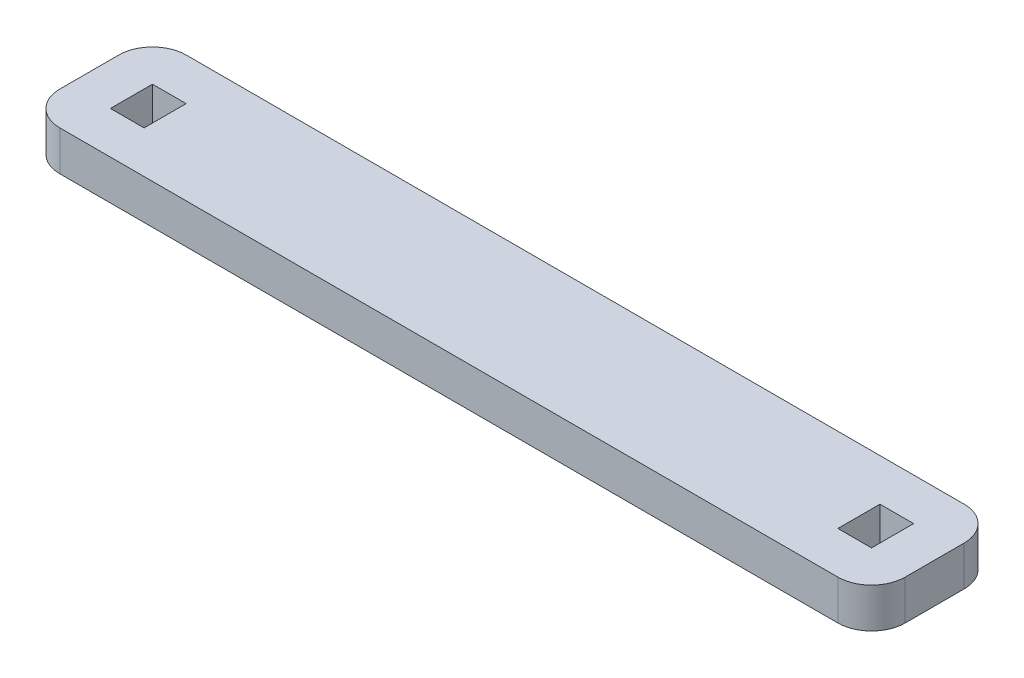
SolidWorks part; units mm, degrees
ref_plane "Front Plane" through (0, 0, 0) normal (0, 0, 1) x (1, 0, 0)
ref_plane "Top Plane" through (0, 0, 0) normal (0, 1, 0) x (1, 0, 0)
ref_plane "Right Plane" through (0, 0, 0) normal (1, 0, 0) x (0, 0, -1)
sketch "Sketch1" plane through (0, 0, 0) normal (0, 1, 0) x (1, 0, 0)
  line L0 (-27.432, 0) -> (27.432, 0) construction
  line L6 (31.877, -4.7625) -> (-31.877, -4.7625)
  line L7 (-26.162, -1.5875) -> (-28.702, -1.5875)
  line L8 (-26.162, -1.5875) -> (-26.162, 1.5875)
  line L9 (-26.162, 1.5875) -> (-28.702, 1.5875)
  line L10 (-28.702, -1.5875) -> (-28.702, 1.5875)
  line L11 (-26.162, -1.5875) -> (-28.702, 1.5875) construction
  line L12 (-26.162, 1.5875) -> (-28.702, -1.5875) construction
  line L13 (28.702, -1.5875) -> (26.162, -1.5875)
  line L14 (28.702, -1.5875) -> (28.702, 1.5875)
  line L15 (28.702, 1.5875) -> (26.162, 1.5875)
  line L16 (26.162, -1.5875) -> (26.162, 1.5875)
  line L17 (28.702, -1.5875) -> (26.162, 1.5875) construction
  line L18 (28.702, 1.5875) -> (26.162, -1.5875) construction
  line L19 (31.877, -4.7625) -> (31.877, 4.7625)
  line L20 (31.877, 4.7625) -> (-31.877, 4.7625)
  line L21 (-31.877, -4.7625) -> (-31.877, 4.7625)
  line L22 (31.877, -4.7625) -> (-31.877, 4.7625) construction
  line L23 (31.877, 4.7625) -> (-31.877, -4.7625) construction
  point P0 (0, 0)
  point P1 (0, 0)
  point P6 (-27.432, 0)
  point P11 (27.432, 0)
  dimension "D1" = 9.525
  dimension "D2" = 3.175
  dimension "D3" = 2.54
  dimension "D4" = 54.864
  dimension "D5" = 3.175
extrude "Boss-Extrude1" add sketch "Sketch1" along normal mid plane 3
fillet "Fillet1" radius 2.54 4 edges at (-31.877, 0, -4.7625) (31.877, 0, -4.7625) (31.877, 0, 4.7625) (-31.877, 0, 4.7625)
